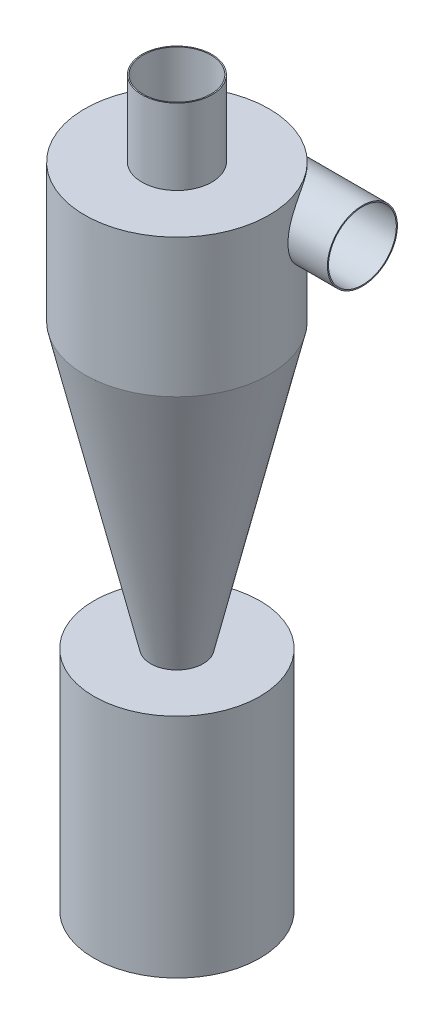
SolidWorks part; units mm, degrees
ref_plane "Front Plane" through (0, 0, 0) normal (0, 0, 1) x (1, 0, 0)
ref_plane "Top Plane" through (0, 0, 0) normal (0, 1, 0) x (1, 0, 0)
ref_plane "Right Plane" through (0, 0, 0) normal (1, 0, 0) x (0, 0, -1)
sketch "Sketch1" plane through (0, 0, 0) normal (0, 0, 1) x (1, 0, 0)
  line L0 (-100, 703.2512) -> (-38, 703.2512)
  line L1 (0, 0) -> (0, 67.6874) construction
  line L3 (-100, 553.2512) -> (-100, 703.2512)
  line L4 (0, 1.2) -> (-88.8, 1.2)
  line L5 (-100, 553.2512) -> (-28.5225, 246.0174)
  line L9 (0, 0) -> (-90, 0)
  line L10 (-90, 0) -> (-90, 246.0174)
  line L11 (-90, 246.0174) -> (-28.5225, 246.0174)
  line L12 (-88.8, 1.2) -> (-88.8, 244.8174)
  line L13 (-38, 631.008) -> (-38, 702.0512)
  line L17 (-88.8, 244.8174) -> (-27.0113, 244.8174)
  line L18 (-98.8, 553.3889) -> (-27.0113, 244.8174)
  line L19 (-98.8, 553.3889) -> (-98.8, 702.0512)
  line L20 (-98.8, 702.0512) -> (-38, 702.0512)
  line L21 (-36.8, 631.008) -> (-36.8, 785.358)
  line L22 (-38, 785.358) -> (-36.8, 785.358)
  line L23 (-38, 631.008) -> (-36.8, 631.008)
  line L24 (-38, 703.2512) -> (-38, 785.358)
  line L25 (0, 1.2) -> (0, 0)
  line L26 (-38, 631.008) -> (-38, 785.358) construction
  point P19 (0, 0)
  point P21 (0, 0)
  point P22 (0, 0)
  point P23 (-98.8, 244.8174)
  dimension "D1" = 1.2
  dimension "D2" = 1.2
  dimension "D3" = 90
revolve "Revolve1" add sketch "Sketch1" angle 360 about L1
ref_plane "Plane1" through (140, 0, 0) normal (1, 0, 0) x (0, 0, -1)
sketch "Sketch2" plane through (140, 0, 0) normal (1, 0, 0) x (0, 0, -1)
  circle A0 centre (61.2787, 663.7871) radius 38
  circle A1 centre (61.2787, 663.7871) radius 36.8
  point P2 (61.2787, 663.7871)
  dimension "D1" = 76
  dimension "D2" = 1.2
extrude "Boss-Extrude1" add sketch "Sketch2" against normal up to next
